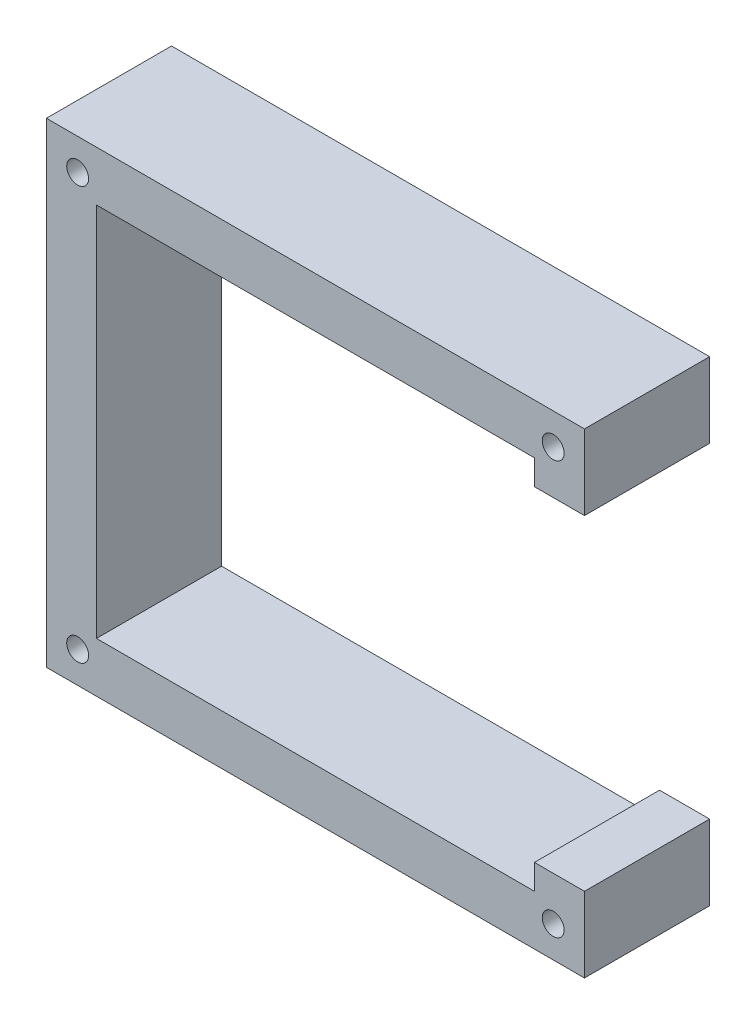
SolidWorks part; units mm, degrees
material "PMMA"
ref_plane "前视基准面" through (0, 0, 0) normal (0, 0, 1) x (1, 0, 0)
ref_plane "上视基准面" through (0, 0, 0) normal (0, 1, 0) x (1, 0, 0)
ref_plane "右视基准面" through (0, 0, 0) normal (1, 0, 0) x (0, 0, -1)
sketch "草图1" plane through (0, 0, 0) normal (0, 0, 1) x (1, 0, 0)
  line L0 (-43, 38) -> (-43, -38)
  line L1 (-35, 30) -> (35, 30)
  line L2 (-35, 30) -> (-35, -30)
  line L3 (-35, -30) -> (35, -30)
  line L4 (35, 30) -> (35, -30)
  line L5 (-35, 30) -> (35, -30) construction
  line L6 (-35, -30) -> (35, 30) construction
  line L7 (-43, -38) -> (43, -38)
  line L8 (43, 38) -> (43, -38)
  line L9 (-43, 38) -> (43, 38)
  line L10 (35, 30) -> (43, 38) construction
  line L11 (35, -30) -> (43, -38) construction
  line L12 (-35, -30) -> (-43, -38) construction
  line L13 (-35, 30) -> (-43, 38) construction
  line L14 (-43, 38) -> (-43, 33) construction
  line L15 (-43, 33) -> (-38, 33) construction
  line L16 (-43, 0) -> (43, 0) construction
  line L17 (0, -30) -> (0, 30) construction
  circle A0 centre (-38, 33) radius 1.75
  circle A1 centre (38, 33) radius 1.75
  circle A2 centre (38, -33) radius 1.75
  circle A3 centre (-38, -33) radius 1.75
  point P0 (0, 0)
  dimension "D1" = 8
extrude "凸台-拉伸1" add sketch "草图1" along normal blind 20
ref_plane "基准面1" through (0, 0, 0) normal (0, 0, -1) x (-1, 0, 0)
sketch "草图2" plane through (0, 0, 0) normal (0, 0, -1) x (-1, 0, 0)
  line L0 (-43, 26) -> (-35, 26)
  line L1 (-35, 30) -> (-35, -30) construction
  line L2 (-35, 26) -> (-35, 30)
  line L3 (-35, -30) -> (-35, -26)
  line L4 (43, 38) -> (-43, 38)
  line L5 (-43, 38) -> (-43, -38)
  line L6 (-43, -38) -> (43, -38)
  line L7 (43, -38) -> (43, 38)
  line L8 (43, 38) -> (-43, 38)
  line L9 (-43, 38) -> (-43, -38)
  line L10 (-43, -38) -> (43, -38)
  line L11 (43, -38) -> (43, 38)
  line L12 (-35, -26) -> (-43, -26)
  line L13 (-43, -26) -> (-43, 26)
  line L14 (-35, 26) -> (-35, -26)
  dimension "D1" = 0
extrude "切除-拉伸1" cut sketch "草图2" against normal up to next contours L14 L0 L9 L12
